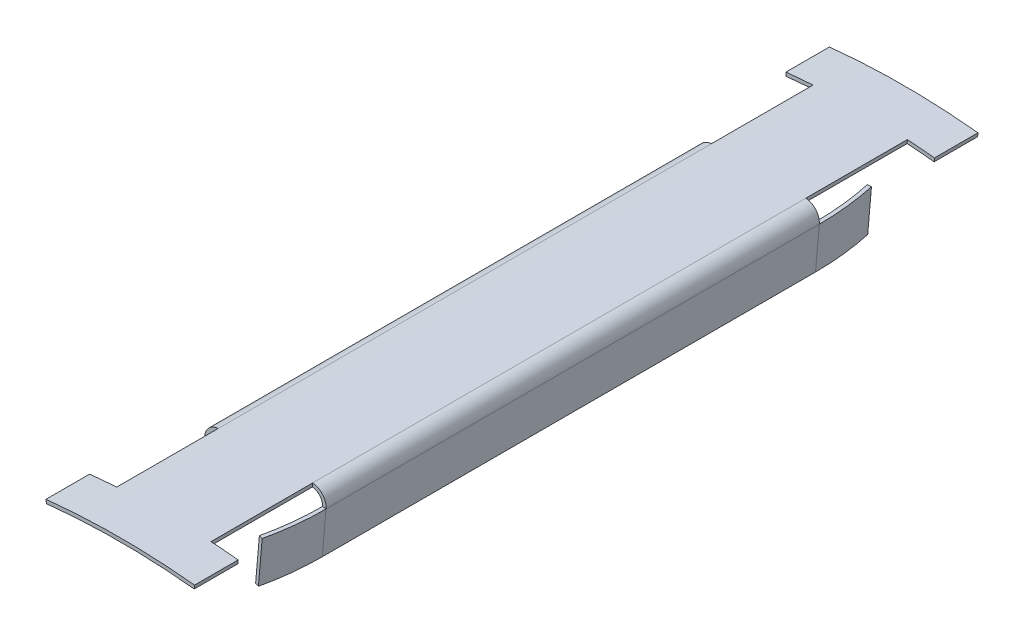
SolidWorks part; units mm, degrees
ref_plane "Plan de face" through (0, 0, 0) normal (0, 0, 1) x (1, 0, 0)
ref_plane "Plan de dessus" through (0, 0, 0) normal (0, 1, 0) x (1, 0, 0)
ref_plane "Plan de droite" through (0, 0, 0) normal (1, 0, 0) x (0, 0, -1)
sketch "Esquisse1" plane through (0, 0, 0) normal (0, 0, 1) x (1, 0, 0)
  line L0 (0, 0) -> (0, 68.6027) construction
  line L1 (0, 0) -> (-6.6602, 76.1263) construction
  line L2 (0, 0) -> (6.4545, 73.7754) construction
  line L3 (-3.9335, 47.8288) -> (-3.672, 44.84)
  line L4 (-3.672, 44.84) -> (-3.9211, 44.8182)
  line L5 (-3.9211, 44.8182) -> (-4.1826, 47.807)
  line L9 (0, 48.75) -> (0, 49)
  arc A0 (0, 49) -> (-3.2528, 48.8919) centre (0, 0) ccw
  arc A1 (0, 48.75) -> (-3.2362, 48.6425) centre (0, 0) ccw
  arc A2 (-3.2362, 48.6425) -> (-3.9335, 47.8288) centre (-3.1864, 47.8941) ccw
  arc A3 (-4.1826, 47.807) -> (-3.2528, 48.8919) centre (-3.1864, 47.8941) cw
  dimension "D1" = 98
  dimension "D3" = 97.5
  dimension "D6" = 4
  dimension "D5" = 1
  dimension "D2" = 5
  dimension "D4" = 5
extrude "Extrusion1" add sketch "Esquisse1" along normal blind 34
sketch "Esquisse2" plane through (-3.9211, 44.8182, 0) normal (0.0872, -0.9962, 0) x (0.9962, 0.0872, 0)
  line L0 (0.25, 34) -> (0.25, 0) construction
  line L1 (0, 34) -> (0.25, 34)
  line L2 (0.4041, 38) -> (0.649, 37.95)
  line L3 (0, 17) -> (3.9758, 17) construction
  line L4 (0, 34) -> (0, 0) construction
  line L5 (0.4041, -4) -> (0.649, -3.95)
  line L6 (0, 0) -> (0.25, 0)
  arc A0 (0.4041, 38) -> (0, 34) centre (20, 34) ccw
  arc A1 (0.649, 37.95) -> (0.25, 34) centre (20, 34) ccw
  arc A2 (0.649, -3.95) -> (0.25, 0) centre (20, 0) cw
  arc A3 (0.4041, -4) -> (0, 0) centre (20, 0) cw
  dimension "D1" = 20
  dimension "D2" = 4
extrude "Extrusion2" add sketch "Esquisse2" against normal blind 3
sketch "Esquisse3" plane through (0, 0, 0) normal (0, 0, -1) x (-1, 0, 0)
  line L0 (3.2362, 48.6425) -> (3.2528, 48.8919)
  line L4 (3.9335, 47.8288) -> (3.9335, 47.8285)
  line L5 (3.9335, 47.8285) -> (4.1825, 47.8068)
  line L6 (4.1825, 47.8068) -> (4.1826, 47.807)
  line L7 (0, 49) -> (0, 48.75)
  line L11 (0, 49) -> (0, 48.75)
  arc A4 (4.1826, 47.807) -> (3.2528, 48.8919) centre (3.1864, 47.8941) ccw
  arc A5 (3.2528, 48.8919) -> (0, 49) centre (0, 0) ccw
  arc A6 (3.2362, 48.6425) -> (0, 48.75) centre (0, 0) ccw
  arc A7 (3.9335, 47.8288) -> (3.2362, 48.6425) centre (3.1864, 47.8941) ccw
  arc A9 (3.2528, 48.8919) -> (0, 49) centre (0, 0) ccw
  arc A10 (3.2362, 48.6425) -> (0, 48.75) centre (0, 0) ccw
  dimension "D1" = 0
extrude "Extrusion3" add sketch "Esquisse3" along normal blind 10
sketch "Esquisse4" plane through (0, 0, 34) normal (0, 0, 1) x (1, 0, 0)
  line L0 (-3.2362, 48.6425) -> (-3.2528, 48.8919)
  line L4 (-4.1826, 47.807) -> (-4.1825, 47.8068)
  line L5 (-4.1825, 47.8068) -> (-3.9335, 47.8285)
  line L6 (-3.9335, 47.8285) -> (-3.9335, 47.8288)
  line L7 (0, 48.75) -> (0, 49)
  line L11 (0, 48.75) -> (0, 49)
  arc A4 (-3.2362, 48.6425) -> (-3.9335, 47.8288) centre (-3.1864, 47.8941) ccw
  arc A5 (0, 48.75) -> (-3.2362, 48.6425) centre (0, 0) ccw
  arc A6 (0, 49) -> (-3.2528, 48.8919) centre (0, 0) ccw
  arc A7 (-3.2528, 48.8919) -> (-4.1826, 47.807) centre (-3.1864, 47.8941) ccw
  arc A9 (0, 48.75) -> (-3.2362, 48.6425) centre (0, 0) ccw
  arc A10 (0, 49) -> (-3.2528, 48.8919) centre (0, 0) ccw
  dimension "D1" = 0
extrude "Extrusion4" add sketch "Esquisse4" along normal blind 10
sketch "Esquisse5" plane through (0, 0, 44) normal (0, 0, 1) x (1, 0, 0)
  line L0 (-5.1219, 48.7316) -> (-5.0958, 48.4829)
  line L1 (0, 49) -> (0, 48.75)
  arc A0 (0, 49) -> (-5.1219, 48.7316) centre (0, 0) ccw
  arc A1 (0, 49) -> (-3.2528, 48.8919) centre (0, 0) ccw construction
  arc A2 (0, 48.75) -> (-5.0958, 48.4829) centre (0, 0) ccw
  arc A3 (0, 48.75) -> (-3.2362, 48.6425) centre (0, 0) ccw construction
  dimension "D1" = 6
extrude "Extrusion5" add sketch "Esquisse5" against normal blind 3
sketch "Esquisse6" plane through (0, 0, -10) normal (0, 0, -1) x (-1, 0, 0)
  line L2 (0, 49) -> (0, 48.75)
  line L3 (5.0958, 48.4829) -> (5.1219, 48.7316)
  line L4 (0, 49) -> (0, 48.75)
  line L5 (5.0958, 48.4829) -> (5.1219, 48.7316)
  arc A2 (5.0958, 48.4829) -> (0, 48.75) centre (0, 0) ccw
  arc A3 (5.1219, 48.7316) -> (0, 49) centre (0, 0) ccw
  arc A4 (5.0958, 48.4829) -> (0, 48.75) centre (0, 0) ccw
  arc A5 (5.1219, 48.7316) -> (0, 49) centre (0, 0) ccw
  dimension "D1" = 0
extrude "Extrusion6" add sketch "Esquisse6" against normal blind 3
mirror "Symétrie1" about plane through (0, 48.75, 34) normal (-1, 0, 0) of "Extrusion1", "Extrusion2", "Extrusion3", "Extrusion4", "Extrusion5", "Extrusion6"
